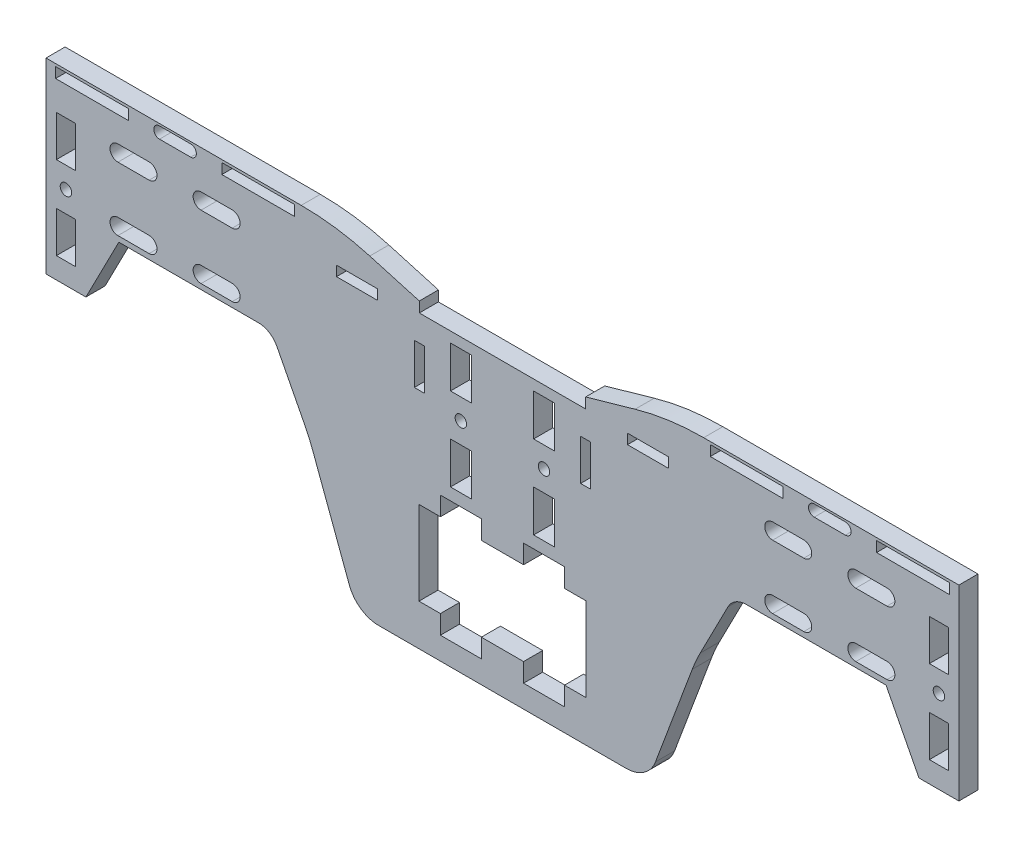
SolidWorks part; units mm, degrees
ref_plane "Front Plane" through (0, 0, 0) normal (0, 0, 1) x (1, 0, 0)
ref_plane "Top Plane" through (0, 0, 0) normal (0, 1, 0) x (1, 0, 0)
ref_plane "Right Plane" through (0, 0, 0) normal (1, 0, 0) x (0, 0, -1)
sketch "Sketch1" plane through (0, 0, 0) normal (0, 0, 1) x (1, 0, 0)
  line L0 (25.4, 66.675) -> (-25.4, 66.675) construction
  line L1 (25.5, -12.8) -> (18.95, -12.8)
  line L2 (25.5, -12.8) -> (25.5, -6.25)
  line L3 (-25.5, 12.8) -> (-18.95, 12.8)
  line L4 (-25.5, -12.8) -> (-25.5, -6.25)
  line L5 (25.5, -12.8) -> (-25.5, 12.8) construction
  line L6 (25.5, 12.8) -> (-25.5, -12.8) construction
  line L7 (0, 0) -> (0, 66.675) construction
  line L8 (25.4, 63.5) -> (-25.4, 63.5)
  line L9 (95.25, 101.6) -> (95.25, -30.1359) construction
  line L10 (19.05, 101.6) -> (171.45, 101.6) construction
  line L11 (171.45, 122.2375) -> (19.05, 122.2375) construction
  line L12 (171.45, 122.2375) -> (171.45, 80.9625) construction
  line L13 (171.45, 80.9625) -> (112.7125, 80.9625) construction
  line L14 (19.05, 122.2375) -> (19.05, 80.9625) construction
  line L15 (171.45, 122.2375) -> (19.05, 80.9625) construction
  line L16 (171.45, 80.9625) -> (19.05, 122.2375) construction
  line L17 (77.7875, 80.9625) -> (19.05, 80.9625) construction
  line L18 (77.7875, 69.9655) -> (74.2442, 69.9655) construction
  line L19 (112.7125, 69.9655) -> (112.7125, 80.9625) construction
  line L20 (63.246, 14.9745) -> (74.2442, 36.3359) construction
  line L21 (77.7875, 69.9655) -> (77.7875, 80.9625) construction
  line L22 (112.7125, 69.9655) -> (77.7875, 80.9625) construction
  line L23 (112.7125, 80.9625) -> (77.7875, 69.9655) construction
  line L24 (116.2558, 36.3359) -> (74.2442, 36.3359) construction
  line L25 (116.2558, 36.3359) -> (116.2558, 69.9655) construction
  line L26 (116.2558, 69.9655) -> (112.7125, 69.9655) construction
  line L27 (74.2442, 36.3359) -> (74.2442, 69.9655) construction
  line L28 (116.2558, 36.3359) -> (74.2442, 69.9655) construction
  line L29 (116.2558, 69.9655) -> (74.2442, 36.3359) construction
  line L30 (127.254, -75.2463) -> (63.246, -75.2463) construction
  line L31 (127.254, -75.2463) -> (127.254, 14.9745) construction
  line L32 (127.254, 14.9745) -> (63.246, 14.9745) construction
  line L33 (63.246, -75.2463) -> (63.246, 14.9745) construction
  line L34 (127.254, -75.2463) -> (63.246, 14.9745) construction
  line L35 (127.254, 14.9745) -> (63.246, -75.2463) construction
  line L36 (127.254, 14.9745) -> (116.2558, 36.3359) construction
  line L37 (74.2442, 59.7801) -> (116.2558, 59.7801) construction
  line L38 (74.2442, 40.3491) -> (116.2558, 40.3491) construction
  line L39 (-6.45, 12.8) -> (6.45, 12.8)
  line L40 (-6.45, 18.542) -> (-18.95, 18.542)
  line L41 (-6.45, 18.542) -> (-6.45, 12.8)
  line L42 (18.95, 18.542) -> (18.95, 12.8)
  line L43 (-18.95, 18.542) -> (-18.95, 12.8)
  line L44 (-6.45, 18.542) -> (-18.95, 12.8) construction
  line L45 (-6.45, 12.8) -> (-18.95, 18.542) construction
  line L46 (-25.5, 0) -> (25.5, 0) construction
  line L47 (6.45, 18.542) -> (6.45, 12.8)
  line L48 (6.45, 18.542) -> (18.95, 12.8) construction
  line L49 (6.45, 12.8) -> (18.95, 18.542) construction
  line L50 (6.45, 18.542) -> (18.95, 18.542)
  line L51 (18.95, 12.8) -> (25.5, 12.8)
  line L52 (44.45, -6.858) -> (34.925, -18.542) construction
  line L53 (44.45, 18.542) -> (34.925, 18.542)
  line L54 (44.45, 18.542) -> (44.45, 6.858)
  line L55 (44.45, 6.858) -> (34.925, 6.858)
  line L56 (34.925, 18.542) -> (34.925, 6.858)
  line L57 (44.45, 18.542) -> (34.925, 6.858) construction
  line L58 (44.45, 6.858) -> (34.925, 18.542) construction
  line L59 (44.45, -18.542) -> (34.925, -6.858) construction
  line L60 (34.925, -18.542) -> (34.925, -6.858)
  line L61 (44.45, -6.858) -> (34.925, -6.858)
  line L62 (44.45, -18.542) -> (44.45, -6.858)
  line L63 (44.45, -18.542) -> (34.925, -18.542)
  line L64 (-44.45, -18.542) -> (-34.925, -6.858) construction
  line L65 (-44.45, 6.858) -> (-34.925, 18.542) construction
  line L66 (-44.45, 18.542) -> (-34.925, 6.858) construction
  line L67 (0, 0) -> (0, -30.1681) construction
  line L68 (-44.45, -6.858) -> (-34.925, -18.542) construction
  line L69 (-44.45, -18.542) -> (-34.925, -18.542)
  line L70 (-44.45, -18.542) -> (-44.45, -6.858)
  line L71 (-44.45, -6.858) -> (-34.925, -6.858)
  line L72 (-34.925, -18.542) -> (-34.925, -6.858)
  line L73 (-34.925, 18.542) -> (-34.925, 6.858)
  line L74 (6.45, -12.8) -> (18.95, -18.542) construction
  line L75 (6.45, -18.542) -> (18.95, -12.8) construction
  line L76 (-6.45, -12.8) -> (-18.95, -18.542) construction
  line L77 (-6.45, -18.542) -> (-18.95, -12.8) construction
  line L78 (-44.45, 6.858) -> (-34.925, 6.858)
  line L79 (44.45, -25.4) -> (-44.45, -25.4)
  line L80 (-44.45, 18.542) -> (-44.45, 6.858)
  line L81 (-44.45, 18.542) -> (-34.925, 18.542)
  line L82 (-12.7, 63.5) -> (-12.7, 47.625) construction
  line L83 (-15.875, 22.225) -> (-9.525, 22.225)
  line L84 (-15.875, 47.625) -> (-9.525, 47.625)
  line L85 (-15.875, 47.625) -> (-15.875, 60.325)
  line L86 (-15.875, 60.325) -> (-9.525, 60.325)
  line L87 (-9.525, 47.625) -> (-9.525, 60.325)
  line L88 (-15.875, 47.625) -> (-9.525, 60.325) construction
  line L89 (-15.875, 60.325) -> (-9.525, 47.625) construction
  line L90 (6.45, -18.542) -> (18.95, -18.542)
  line L91 (6.45, -18.542) -> (6.45, -12.8)
  line L92 (-18.95, -18.542) -> (-18.95, -12.8)
  line L93 (18.95, -18.542) -> (18.95, -12.8)
  line L94 (-6.45, -18.542) -> (-6.45, -12.8)
  line L95 (-6.45, -18.542) -> (-18.95, -18.542)
  line L96 (-18.95, -12.8) -> (-25.5, -12.8)
  line L97 (6.45, -12.8) -> (-6.45, -12.8)
  line L98 (-25.5, 6.25) -> (-25.5, 12.8)
  line L99 (-31.242, -6.25) -> (-25.5, -6.25)
  line L100 (-31.242, -6.25) -> (-31.242, 6.25)
  line L101 (-31.242, 6.25) -> (-25.5, 6.25)
  line L102 (31.242, 6.25) -> (25.5, 6.25)
  line L103 (-31.242, -6.25) -> (-25.5, 6.25) construction
  line L104 (-31.242, 6.25) -> (-25.5, -6.25) construction
  line L105 (31.242, -6.25) -> (25.5, -6.25)
  line L106 (31.242, -6.25) -> (25.5, 6.25) construction
  line L107 (31.242, 6.25) -> (25.5, -6.25) construction
  line L108 (31.242, -6.25) -> (31.242, 6.25)
  line L109 (25.5, 6.25) -> (25.5, 12.8)
  line L110 (-15.875, 22.225) -> (-15.875, 34.925)
  line L111 (-15.875, 34.925) -> (-9.525, 34.925)
  line L112 (82.55, 59.7801) -> (92.075, 59.7801) construction
  line L113 (82.55, 62.1931) -> (92.075, 62.1931)
  line L114 (82.55, 57.3671) -> (92.075, 57.3671)
  line L115 (82.55, 40.3491) -> (92.075, 40.3491) construction
  line L116 (82.55, 42.7621) -> (92.075, 42.7621)
  line L117 (82.55, 37.9361) -> (92.075, 37.9361)
  line L118 (107.95, 59.7801) -> (117.475, 59.7801) construction
  line L119 (107.95, 62.1931) -> (117.475, 62.1931)
  line L120 (107.95, 57.3671) -> (117.475, 57.3671)
  line L121 (107.95, 40.3491) -> (117.475, 40.3491) construction
  line L122 (107.95, 42.7621) -> (117.475, 42.7621)
  line L123 (107.95, 37.9361) -> (117.475, 37.9361)
  line L124 (63.8955, 73.1405) -> (128.9432, 73.1405) construction
  line L125 (63.5, 73.1405) -> (76.2, 73.1405)
  line L126 (63.5, 73.1405) -> (63.5, 69.9655)
  line L127 (114.3, 73.1405) -> (127, 73.1405)
  line L128 (63.5, 69.9655) -> (76.2, 69.9655)
  line L129 (63.5, 69.9655) -> (76.2, 73.1405) construction
  line L130 (63.5, 73.1405) -> (76.2, 69.9655) construction
  line L131 (114.3, 69.9655) -> (127, 69.9655)
  line L132 (76.2, 73.1405) -> (85.725, 73.1405)
  line L133 (76.2, 69.9655) -> (85.725, 69.9655)
  line L134 (85.725, 73.1405) -> (85.725, 69.9655)
  line L135 (114.3, 73.1405) -> (114.3, 69.9655)
  line L136 (127, 73.1405) -> (136.525, 73.1405)
  line L137 (136.525, 73.1405) -> (136.525, 69.9655)
  line L138 (127, 69.9655) -> (136.525, 69.9655)
  line L139 (-28.371, 0) -> (-28.371, 63.5) construction
  line L140 (-31.242, 44.55) -> (-25.5, 44.55)
  line L141 (-31.242, 31.65) -> (-25.5, 31.65)
  line L142 (-31.242, 31.65) -> (-31.242, 19.15)
  line L143 (-31.242, 19.15) -> (-25.5, 19.15)
  line L144 (-25.5, 31.65) -> (-25.5, 19.15)
  line L145 (-31.242, 31.65) -> (-25.5, 19.15) construction
  line L146 (-31.242, 19.15) -> (-25.5, 31.65) construction
  line L147 (-31.242, 57.05) -> (-31.242, 44.55)
  line L148 (-31.242, 57.05) -> (-25.5, 57.05)
  line L149 (-25.5, 57.05) -> (-25.5, 44.55)
  line L150 (28.371, 0) -> (28.371, 63.5) construction
  line L151 (31.242, 19.15) -> (25.5, 31.65) construction
  line L152 (31.242, 31.65) -> (25.5, 19.15) construction
  line L153 (25.5, 57.05) -> (25.5, 44.55)
  line L154 (31.242, 57.05) -> (25.5, 57.05)
  line L155 (31.242, 57.05) -> (31.242, 44.55)
  line L156 (25.5, 31.65) -> (25.5, 19.15)
  line L157 (31.242, 19.15) -> (25.5, 19.15)
  line L158 (31.242, 31.65) -> (31.242, 19.15)
  line L159 (31.242, 31.65) -> (25.5, 31.65)
  line L160 (31.242, 44.55) -> (25.5, 44.55)
  line L161 (50.8, 73.9342) -> (139.446, 73.9342)
  line L162 (25.4, 63.5) -> (25.4, 66.675)
  line L163 (25.4, 66.675) -> (50.8, 73.9342)
  line L164 (44.45, -25.4) -> (59.0461, 13.7533)
  line L165 (70.6731, 36.3359) -> (117.1876, 36.3359)
  line L166 (59.0461, 13.7533) -> (70.6731, 36.3359)
  line L167 (133.35, 73.9342) -> (133.35, 48.6342) construction
  line L168 (60.4232, 16.4279) -> (71.4214, 37.7893) construction
  line L169 (130.429, 35.7342) -> (136.271, 35.7342)
  line L170 (-25.4, 63.5) -> (-25.4, 66.675)
  line L171 (-25.4, 66.675) -> (-50.8, 73.9342)
  line L172 (-63.5, 73.1405) -> (-76.2, 69.9655) construction
  line L173 (-63.5, 69.9655) -> (-76.2, 73.1405) construction
  line L174 (-63.8955, 73.1405) -> (-128.9432, 73.1405) construction
  line L175 (-74.2442, 40.3491) -> (-116.2558, 40.3491) construction
  line L176 (-74.2442, 59.7801) -> (-116.2558, 59.7801) construction
  line L177 (-127.254, 14.9745) -> (-116.2558, 36.3359) construction
  line L178 (-127.254, 14.9745) -> (-63.246, -75.2463) construction
  line L179 (-127.254, -75.2463) -> (-63.246, 14.9745) construction
  line L180 (-63.246, -75.2463) -> (-63.246, 14.9745) construction
  line L181 (-127.254, 14.9745) -> (-63.246, 14.9745) construction
  line L182 (-127.254, -75.2463) -> (-127.254, 14.9745) construction
  line L183 (-127.254, -75.2463) -> (-63.246, -75.2463) construction
  line L184 (-116.2558, 69.9655) -> (-74.2442, 36.3359) construction
  line L185 (-116.2558, 36.3359) -> (-74.2442, 69.9655) construction
  line L186 (-74.2442, 36.3359) -> (-74.2442, 69.9655) construction
  line L187 (-116.2558, 69.9655) -> (-112.7125, 69.9655) construction
  line L188 (-116.2558, 36.3359) -> (-116.2558, 69.9655) construction
  line L189 (-116.2558, 36.3359) -> (-74.2442, 36.3359) construction
  line L190 (-112.7125, 80.9625) -> (-77.7875, 69.9655) construction
  line L191 (-112.7125, 69.9655) -> (-77.7875, 80.9625) construction
  line L192 (-77.7875, 69.9655) -> (-77.7875, 80.9625) construction
  line L193 (-63.246, 14.9745) -> (-74.2442, 36.3359) construction
  line L194 (-112.7125, 69.9655) -> (-112.7125, 80.9625) construction
  line L195 (-77.7875, 69.9655) -> (-74.2442, 69.9655) construction
  line L196 (-77.7875, 80.9625) -> (-19.05, 80.9625) construction
  line L197 (-171.45, 80.9625) -> (-19.05, 122.2375) construction
  line L198 (-171.45, 122.2375) -> (-19.05, 80.9625) construction
  line L199 (-171.45, 80.9625) -> (-112.7125, 80.9625) construction
  line L200 (-171.45, 122.2375) -> (-171.45, 80.9625) construction
  line L201 (-171.45, 122.2375) -> (-19.05, 122.2375) construction
  line L202 (-19.05, 101.6) -> (-171.45, 101.6) construction
  line L203 (-95.25, 101.6) -> (-95.25, -30.1359) construction
  line L204 (130.429, 61.1342) -> (136.271, 61.1342)
  line L205 (130.429, 61.1342) -> (130.429, 48.6342)
  line L206 (-59.0461, 13.7533) -> (-70.6731, 36.3359)
  line L207 (-70.6731, 36.3359) -> (-117.1876, 36.3359)
  line L208 (-44.45, -25.4) -> (-59.0461, 13.7533)
  line L209 (-50.8, 73.9342) -> (-139.446, 73.9342)
  line L210 (-127, 69.9655) -> (-136.525, 69.9655)
  line L211 (-136.525, 73.1405) -> (-136.525, 69.9655)
  line L212 (-127, 73.1405) -> (-136.525, 73.1405)
  line L213 (-114.3, 73.1405) -> (-114.3, 69.9655)
  line L214 (-85.725, 73.1405) -> (-85.725, 69.9655)
  line L215 (-76.2, 69.9655) -> (-85.725, 69.9655)
  line L216 (-76.2, 73.1405) -> (-85.725, 73.1405)
  line L217 (-114.3, 69.9655) -> (-127, 69.9655)
  line L218 (-63.5, 69.9655) -> (-76.2, 69.9655)
  line L219 (-114.3, 73.1405) -> (-127, 73.1405)
  line L220 (-63.5, 73.1405) -> (-63.5, 69.9655)
  line L221 (-63.5, 73.1405) -> (-76.2, 73.1405)
  line L222 (-107.95, 40.3491) -> (-117.475, 40.3491) construction
  line L223 (-107.95, 42.7621) -> (-117.475, 42.7621)
  line L224 (-107.95, 37.9361) -> (-117.475, 37.9361)
  line L225 (-107.95, 59.7801) -> (-117.475, 59.7801) construction
  line L226 (-107.95, 62.1931) -> (-117.475, 62.1931)
  line L227 (-107.95, 57.3671) -> (-117.475, 57.3671)
  line L228 (-82.55, 40.3491) -> (-92.075, 40.3491) construction
  line L229 (-82.55, 42.7621) -> (-92.075, 42.7621)
  line L230 (-82.55, 37.9361) -> (-92.075, 37.9361)
  line L231 (-82.55, 59.7801) -> (-92.075, 59.7801) construction
  line L232 (-82.55, 62.1931) -> (-92.075, 62.1931)
  line L233 (-82.55, 57.3671) -> (-92.075, 57.3671)
  line L234 (-19.05, 122.2375) -> (-19.05, 80.9625) construction
  line L235 (-25.5, 44.55) -> (-25.5, 31.65) construction
  line L236 (25.5, 31.65) -> (25.5, 44.55) construction
  line L237 (-25.5, 38.1) -> (25.5, 38.1) construction
  line L238 (-9.525, 22.225) -> (-9.525, 34.925)
  line L239 (-15.875, 22.225) -> (-9.525, 34.925) construction
  line L240 (-15.875, 34.925) -> (-9.525, 22.225) construction
  line L241 (-12.7, 34.925) -> (-12.7, 18.542) construction
  line L242 (-12.7, 47.625) -> (-12.7, 34.925) construction
  line L243 (12.7, 47.625) -> (12.7, 34.925) construction
  line L244 (15.875, 34.925) -> (9.525, 22.225) construction
  line L245 (15.875, 22.225) -> (9.525, 34.925) construction
  line L246 (15.875, 60.325) -> (9.525, 47.625) construction
  line L247 (15.875, 47.625) -> (9.525, 60.325) construction
  line L248 (9.525, 22.225) -> (9.525, 34.925)
  line L249 (15.875, 34.925) -> (9.525, 34.925)
  line L250 (15.875, 22.225) -> (15.875, 34.925)
  line L251 (9.525, 47.625) -> (9.525, 60.325)
  line L252 (15.875, 60.325) -> (9.525, 60.325)
  line L253 (15.875, 47.625) -> (15.875, 60.325)
  line L254 (15.875, 47.625) -> (9.525, 47.625)
  line L255 (15.875, 22.225) -> (9.525, 22.225)
  line L256 (-116.2558, 50.75) -> (-74.2442, 50.75) construction
  line L257 (-85.725, 71.553) -> (-114.3, 71.553) construction
  line L258 (-95.25, 71.553) -> (-104.775, 71.553) construction
  line L259 (-95.25, 69.8004) -> (-104.775, 69.8004)
  line L260 (-95.25, 73.3056) -> (-104.775, 73.3056)
  line L261 (50.292, 53.671) -> (50.292, 47.829)
  line L262 (-62.992, 53.671) -> (-50.292, 53.671)
  line L263 (-62.992, 53.671) -> (-62.992, 47.829)
  line L264 (-62.992, 47.829) -> (-50.292, 47.829)
  line L265 (-50.292, 53.671) -> (-50.292, 47.829)
  line L266 (-62.992, 53.671) -> (-50.292, 47.829) construction
  line L267 (-62.992, 47.829) -> (-50.292, 53.671) construction
  line L268 (62.992, 53.671) -> (50.292, 47.829) construction
  line L269 (62.992, 47.829) -> (50.292, 53.671) construction
  line L270 (62.992, 47.829) -> (50.292, 47.829)
  line L271 (62.992, 53.671) -> (62.992, 47.829)
  line L272 (62.992, 53.671) -> (50.292, 53.671)
  line L273 (95.25, 71.553) -> (104.775, 71.553) construction
  line L274 (95.25, 69.8004) -> (104.775, 69.8004)
  line L275 (95.25, 73.3056) -> (104.775, 73.3056)
  line L276 (-56.642, 47.829) -> (-56.642, 53.671) construction
  line L277 (130.429, 48.6342) -> (136.271, 48.6342)
  line L278 (136.271, 61.1342) -> (136.271, 48.6342)
  line L279 (130.429, 61.1342) -> (136.271, 48.6342) construction
  line L280 (130.429, 48.6342) -> (136.271, 61.1342) construction
  line L281 (130.429, 35.7342) -> (130.429, 23.2342)
  line L282 (130.429, 23.2342) -> (136.271, 23.2342)
  line L283 (136.271, 35.7342) -> (136.271, 23.2342)
  line L284 (133.35, 35.7342) -> (133.35, 23.2342) construction
  line L285 (130.429, 35.7342) -> (136.271, 23.2342) construction
  line L286 (130.429, 23.2342) -> (136.271, 35.7342) construction
  line L287 (133.35, 35.7342) -> (133.35, 27.5161) construction
  line L288 (133.35, 35.7342) -> (133.35, 48.6342) construction
  line L289 (139.446, 73.9342) -> (139.446, 16.7842)
  line L290 (139.446, 16.7842) -> (127.254, 16.7842)
  line L291 (127.254, 16.7842) -> (117.1876, 36.3359)
  line L292 (-127.254, 16.7842) -> (-117.1876, 36.3359)
  line L293 (-139.446, 16.7842) -> (-127.254, 16.7842)
  line L294 (-139.446, 73.9342) -> (-139.446, 16.7842)
  line L295 (-133.35, 35.7342) -> (-133.35, 48.6342) construction
  line L296 (-133.35, 35.7342) -> (-133.35, 27.5161) construction
  line L297 (-130.429, 23.2342) -> (-136.271, 35.7342) construction
  line L298 (-130.429, 35.7342) -> (-136.271, 23.2342) construction
  line L299 (-133.35, 35.7342) -> (-133.35, 23.2342) construction
  line L300 (-130.429, 48.6342) -> (-136.271, 61.1342) construction
  line L301 (-130.429, 61.1342) -> (-136.271, 48.6342) construction
  line L302 (-136.271, 35.7342) -> (-136.271, 23.2342)
  line L303 (-130.429, 23.2342) -> (-136.271, 23.2342)
  line L304 (-130.429, 35.7342) -> (-130.429, 23.2342)
  line L305 (-136.271, 61.1342) -> (-136.271, 48.6342)
  line L306 (-130.429, 48.6342) -> (-136.271, 48.6342)
  line L307 (-130.429, 61.1342) -> (-130.429, 48.6342)
  line L308 (-130.429, 61.1342) -> (-136.271, 61.1342)
  line L309 (-130.429, 35.7342) -> (-136.271, 35.7342)
  circle A0 centre (82.55, 59.7801) radius 2.413 construction
  circle A1 centre (107.95, 59.7801) radius 2.413 construction
  circle A2 centre (82.55, 40.3491) radius 2.413 construction
  circle A3 centre (107.95, 40.3491) radius 2.413 construction
  arc A4 (82.55, 62.1931) -> (82.55, 57.3671) centre (82.55, 59.7801) ccw
  arc A5 (92.075, 57.3671) -> (92.075, 62.1931) centre (92.075, 59.7801) ccw
  arc A6 (82.55, 42.7621) -> (82.55, 37.9361) centre (82.55, 40.3491) ccw
  arc A7 (92.075, 37.9361) -> (92.075, 42.7621) centre (92.075, 40.3491) ccw
  arc A8 (107.95, 62.1931) -> (107.95, 57.3671) centre (107.95, 59.7801) ccw
  arc A9 (117.475, 57.3671) -> (117.475, 62.1931) centre (117.475, 59.7801) ccw
  arc A10 (107.95, 42.7621) -> (107.95, 37.9361) centre (107.95, 40.3491) ccw
  arc A11 (117.475, 37.9361) -> (117.475, 42.7621) centre (117.475, 40.3491) ccw
  circle A12 centre (-107.95, 40.3491) radius 2.413 construction
  circle A13 centre (-82.55, 40.3491) radius 2.413 construction
  circle A14 centre (-107.95, 59.7801) radius 2.413 construction
  circle A15 centre (-82.55, 59.7801) radius 2.413 construction
  arc A16 (-107.95, 42.7621) -> (-107.95, 37.9361) centre (-107.95, 40.3491) cw
  arc A17 (-117.475, 37.9361) -> (-117.475, 42.7621) centre (-117.475, 40.3491) cw
  arc A18 (-107.95, 62.1931) -> (-107.95, 57.3671) centre (-107.95, 59.7801) cw
  arc A19 (-117.475, 57.3671) -> (-117.475, 62.1931) centre (-117.475, 59.7801) cw
  arc A20 (-82.55, 42.7621) -> (-82.55, 37.9361) centre (-82.55, 40.3491) cw
  arc A21 (-92.075, 37.9361) -> (-92.075, 42.7621) centre (-92.075, 40.3491) cw
  arc A22 (-82.55, 62.1931) -> (-82.55, 57.3671) centre (-82.55, 59.7801) cw
  arc A23 (-92.075, 57.3671) -> (-92.075, 62.1931) centre (-92.075, 59.7801) cw
  circle A24 centre (0, 101.6) radius 34.925 construction
  circle A25 centre (28.371, 38.1) radius 1.7526
  circle A26 centre (-28.371, 38.1) radius 1.7526
  circle A27 centre (-12.7, 41.275) radius 1.7526
  circle A28 centre (12.7, 41.275) radius 1.7526
  arc A29 (-95.25, 69.8004) -> (-95.25, 73.3056) centre (-95.25, 71.553) ccw
  arc A30 (-104.775, 73.3056) -> (-104.775, 69.8004) centre (-104.775, 71.553) ccw
  arc A31 (95.25, 69.8004) -> (95.25, 73.3056) centre (95.25, 71.553) cw
  arc A32 (104.775, 73.3056) -> (104.775, 69.8004) centre (104.775, 71.553) cw
  circle A33 centre (-72.517, 50.75) radius 1.7526
  circle A34 centre (-40.767, 50.75) radius 1.7526
  circle A35 centre (40.767, 50.75) radius 1.7526
  circle A36 centre (72.517, 50.75) radius 1.7526
  circle A37 centre (133.35, 42.1842) radius 1.7526
  circle A38 centre (-133.35, 42.1842) radius 1.7526
  point P0 (0, 0)
  point P9 (0, 66.675)
  point P14 (0, 63.5)
  point P22 (95.25, 75.464)
  point P27 (95.25, 53.1507)
  point P45 (39.6875, 12.7)
  point P49 (-12.7, 15.671)
  point P60 (12.7, 15.671)
  point P63 (0, 15.671)
  point P70 (39.6875, -12.7)
  point P79 (-39.6875, -12.7)
  point P80 (-39.6875, 12.7)
  point P83 (-12.7, 53.975)
  point P97 (-12.7, 28.575)
  point P100 (0, -15.671)
  point P101 (12.7, -15.671)
  point P102 (-12.7, -15.671)
  point P104 (-28.371, 0)
  point P113 (28.371, 0)
  point P118 (0, -25.4)
  point P119 (87.3125, 59.7801)
  point P124 (87.3125, 40.3491)
  point P135 (112.7125, 59.7801)
  point P140 (112.7125, 40.3491)
  point P146 (69.85, 71.553)
  point P161 (-28.371, 25.4)
  point P180 (28.371, 25.4)
  point P241 (-69.85, 71.553)
  point P243 (-112.7125, 40.3491)
  point P249 (-112.7125, 59.7801)
  point P255 (-87.3125, 40.3491)
  point P261 (-87.3125, 59.7801)
  point P266 (-95.25, 53.1507)
  point P267 (-95.25, 75.464)
  point P292 (12.7, 28.575)
  point P293 (12.7, 53.975)
  point P300 (-100.0125, 71.553)
  point P305 (-56.642, 50.75)
  point P316 (100.0125, 71.553)
  point P331 (133.35, 54.8842)
  point P340 (133.35, 29.4842)
  point P364 (-133.35, 29.4842)
  point P365 (-133.35, 54.8842)
  dimension "D17" = 4.826
  dimension "D33" = 2.413
  dimension "D34" = 2.413
  dimension "D53" = 69.85
  dimension "D56" = 3.5052
  dimension "D61" = 3.5052
  dimension "D64" = 1.7526
  dimension "D69" = 3.5052
  dimension "D74" = 3.5052
  dimension "D1" = 25.6
  dimension "D2" = 51
  dimension "D3" = 50.8
  dimension "D4" = 66.675
  dimension "D5" = 3.175
  dimension "D6" = 152.4
  dimension "D7" = 41.275
  dimension "D9" = 19.05
  dimension "D10" = 10.997
  dimension "D11" = 42.0116
  dimension "D12" = 33.6296
  dimension "D13" = 64.008
  dimension "D14" = 90.2208
  dimension "D15" = 21.3614
  dimension "D16" = 10.1854
  dimension "D18" = 12.7
  dimension "D19" = 19.431
  dimension "D21" = 12.7
  dimension "D22" = 5.742
  dimension "D23" = 12.5
  dimension "D24" = 9.525
  dimension "D25" = 11.684
  dimension "D26" = 39.6875
  dimension "D27" = 6.35
  dimension "D28" = 5.742
  dimension "D29" = 12.5
  dimension "D30" = 25.4
  dimension "D31" = 88.9
  dimension "D32" = 9.525
  dimension "D35" = 9.525
  dimension "D37" = 34.925
  dimension "D38" = 3.175
  dimension "D39" = 3.175
  dimension "D40" = 12.7
  dimension "D41" = 25.4
  dimension "D42" = 9.525
  dimension "D44" = 5.742
  dimension "D45" = 12.5
  dimension "D46" = 25.4
  dimension "D48" = 1.5875
  dimension "D49" = 25.4
  dimension "D51" = 12.192
  dimension "D52" = 3.175
  dimension "D54" = 101.6
  dimension "D55" = 25.4
  dimension "D57" = 9.525
  dimension "D58" = 12.7
  dimension "D59" = 12.7
  dimension "D63" = 9.525
  dimension "D65" = 19.05
  dimension "D66" = 12.7
  dimension "D67" = 5.842
  dimension "D68" = 15.875
  dimension "D70" = 5.842
  dimension "D71" = 12.5
  dimension "D73" = 19.05
  dimension "D75" = 38.1
  dimension "D76" = 12.7
  dimension "D50" = 3.175
  dimension "D20" = 2
  dimension "D36" = 2
  dimension "D43" = 2
  dimension "D47" = 2
  dimension "D60" = 2
  dimension "D72" = 2
extrude "Boss-Extrude1" add sketch "Sketch1" along normal blind 5.842
fillet "Fillet1" radius 6.35 2 edges at (70.6731, 36.3359, 2.921) (-70.6731, 36.3359, 2.921)
fillet "Fillet2" radius 9.525 2 edges at (-44.45, -25.4, 2.921) (44.45, -25.4, 2.921)
fillet "Fillet4" radius 76.2 2 edges at (50.8, 73.9342, 2.921) (-50.8, 73.9342, 2.921)
fillet "Fillet5" radius 50.8 2 edges at (59.0461, 13.7533, 2.921) (-59.0461, 13.7533, 2.921)
sketch "Sketch2" plane through (0, 0, 5.842) normal (0, 0, 1) x (1, 0, 0)
  line L0 (44.45, 6.858) -> (44.45, 18.542) construction
  line L1 (-44.45, 18.542) -> (-34.925, 18.542)
  line L2 (-44.45, 18.542) -> (-44.45, -18.542)
  line L3 (-44.45, -18.542) -> (-34.925, -18.542)
  line L4 (-34.925, 18.542) -> (-34.925, -18.542)
  line L5 (34.925, -18.542) -> (44.45, -18.542)
  line L6 (34.925, -18.542) -> (34.925, 18.542)
  line L7 (34.925, 18.542) -> (44.45, 18.542)
  line L8 (44.45, -18.542) -> (44.45, 18.542)
extrude "Boss-Extrude2" add sketch "Sketch2" against normal up to surface (5.842 mm away) up to face at (-133.35, 54.8842, 0)
sketch "Sketch3" plane through (0, 0, 5.842) normal (0, 0, 1) x (1, 0, 0)
  line L0 (0, 63.5) -> (0, -25.4) construction
  line L1 (-77.0183, 57.907) -> (-37.2922, 57.907)
  line L2 (-77.0183, 57.907) -> (-77.0183, 44.7899)
  line L3 (-77.0183, 44.7899) -> (-37.2922, 44.7899)
  line L4 (-37.2922, 57.907) -> (-37.2922, 44.7899)
  line L5 (-31.242, 57.05) -> (-25.5, 57.05)
  line L6 (-31.242, 57.05) -> (-31.242, 19.15)
  line L8 (-25.5, 57.05) -> (-25.5, 19.15)
  line L9 (25.4, 63.5) -> (-25.4, 63.5) construction
  line L10 (-37.8355, -25.4) -> (37.8355, -25.4) construction
  line L11 (25.5, 57.05) -> (25.5, 19.15)
  line L13 (31.242, 57.05) -> (31.242, 19.15)
  line L14 (31.242, 57.05) -> (25.5, 57.05)
  line L15 (37.2922, 57.907) -> (37.2922, 44.7899)
  line L16 (77.0183, 44.7899) -> (37.2922, 44.7899)
  line L17 (77.0183, 57.907) -> (77.0183, 44.7899)
  line L18 (77.0183, 57.907) -> (37.2922, 57.907)
  line L21 (-31.242, 19.15) -> (-31.242, -6.25)
  line L22 (-31.242, -6.25) -> (-25.5, -6.25)
  line L23 (-25.5, 19.15) -> (-25.5, -6.25)
  line L24 (25.5, -6.25) -> (31.242, -6.25)
  line L25 (25.5, -6.25) -> (25.5, 19.15)
  line L27 (31.242, -6.25) -> (31.242, 19.15)
extrude "Boss-Extrude3" add sketch "Sketch3" against normal up to surface (5.842 mm away) up to face at (-133.35, 54.8842, 0)
fillet "Fillet6" [suppressed] radius 6.35
fillet "Fillet7" [suppressed] radius 1.5875
sketch "Sketch4" plane through (0, 0, 5.842) normal (0, 0, 1) x (1, 0, 0)
  line L0 (0, 63.5) -> (0, 12.8) construction
  line L1 (25.4, 63.5) -> (-25.4, 63.5) construction
  line L2 (6.45, 12.8) -> (-6.45, 12.8) construction
  line L3 (44.45, 63.5) -> (-44.45, 63.5) construction
  line L4 (-50.7, 63.5) -> (-38.2, 60.452) construction
  line L5 (50.7, 60.452) -> (38.2, 60.452)
  line L6 (50.7, 60.452) -> (50.7, 63.5)
  line L7 (50.7, 63.5) -> (38.2, 63.5)
  line L8 (38.2, 60.452) -> (38.2, 63.5)
  line L9 (50.7, 60.452) -> (38.2, 63.5) construction
  line L10 (50.7, 63.5) -> (38.2, 60.452) construction
  line L11 (-50.7, 60.452) -> (-38.2, 63.5) construction
  line L12 (-38.2, 60.452) -> (-38.2, 63.5)
  line L13 (-50.7, 63.5) -> (-38.2, 63.5)
  line L14 (-50.7, 60.452) -> (-50.7, 63.5)
  line L15 (-50.7, 60.452) -> (-38.2, 60.452)
  line L16 (-25.4, 63.5) -> (-25.4, 49.276) construction
  line L17 (23.876, 55.526) -> (26.924, 43.026) construction
  line L18 (-23.876, 43.026) -> (-26.924, 43.026)
  line L19 (-23.876, 43.026) -> (-23.876, 55.526)
  line L20 (-23.876, 55.526) -> (-26.924, 55.526)
  line L21 (-26.924, 43.026) -> (-26.924, 55.526)
  line L22 (-23.876, 43.026) -> (-26.924, 55.526) construction
  line L23 (-23.876, 55.526) -> (-26.924, 43.026) construction
  line L24 (23.876, 43.026) -> (26.924, 55.526) construction
  line L25 (26.924, 43.026) -> (26.924, 55.526)
  line L26 (23.876, 55.526) -> (26.924, 55.526)
  line L27 (23.876, 43.026) -> (23.876, 55.526)
  line L28 (23.876, 43.026) -> (26.924, 43.026)
  point P6 (44.45, 61.976)
  point P9 (0, 63.5)
  point P14 (44.45, 63.5)
  point P19 (-44.45, 61.976)
  point P20 (0, 61.9125)
  dimension "D1" = 88.9
  dimension "D2" = 3.048
  dimension "D3" = 12.5
  dimension "D4" = 12.7
  dimension "D5" = 19.05
  dimension "D6" = 3.048
  dimension "D7" = 12.5
extrude "Cut-Extrude1" cut sketch "Sketch4" against normal through all
